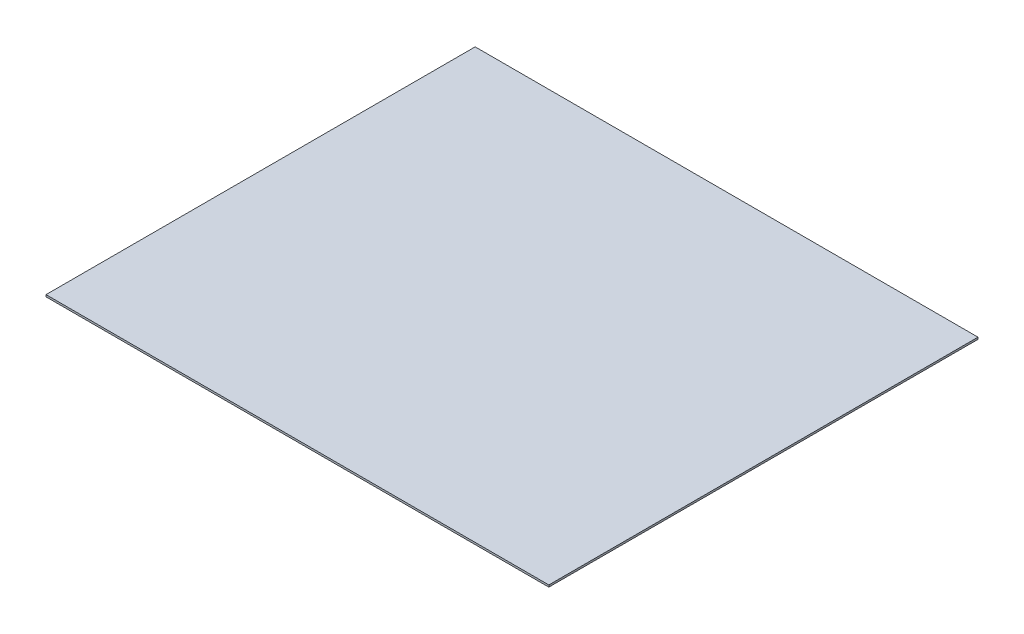
SolidWorks part; units mm, degrees
ref_plane "Front Plane" through (0, 0, 0) normal (0, 0, 1) x (1, 0, 0)
ref_plane "Top Plane" through (0, 0, 0) normal (0, 1, 0) x (1, 0, 0)
ref_plane "Right Plane" through (0, 0, 0) normal (1, 0, 0) x (0, 0, -1)
sketch "Sketch1" plane through (0, 0, 0) normal (0, 1, 0) x (1, 0, 0)
  line L0 (662.94, 632.155) -> (662.94, -66.345) construction
  line L5 (0, 0) -> (662.94, 0)
  line L6 (0, 0) -> (0, 565.81)
  line L7 (0, 565.81) -> (662.94, 565.81)
  line L8 (662.94, 0) -> (662.94, 565.81)
  line L9 (648.97, 565.81) -> (11.43, 565.81) construction
  point P0 (0, 0)
extrude "Boss-Extrude1" add sketch "Sketch1" along normal blind 2.54 contours L6 L5 L8 L7
